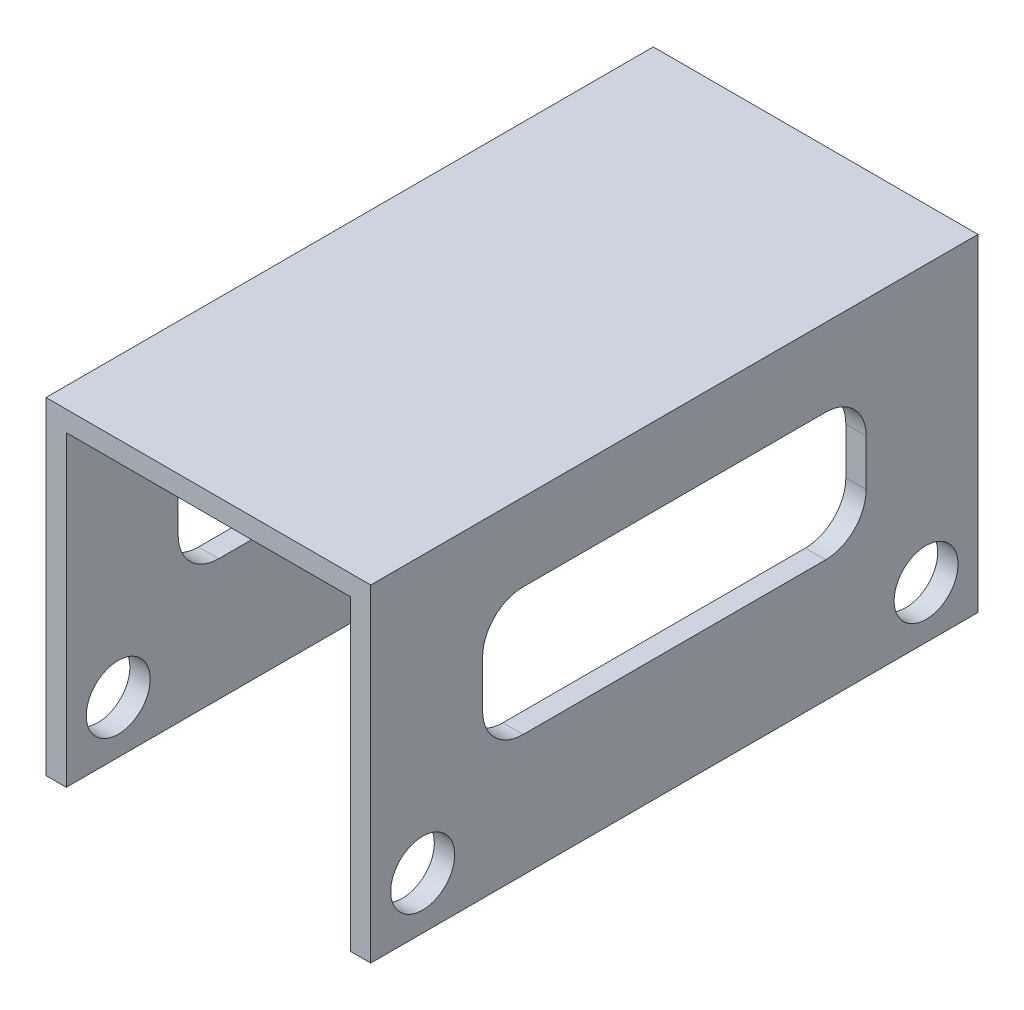
SolidWorks part; units mm, degrees
ref_plane "Front Plane" through (0, 0, 0) normal (0, 0, 1) x (1, 0, 0)
ref_plane "Top Plane" through (0, 0, 0) normal (0, 1, 0) x (1, 0, 0)
ref_plane "Right Plane" through (0, 0, 0) normal (1, 0, 0) x (0, 0, -1)
sketch "Sketch1" plane through (0, 0, 0) normal (0, 0, 1) x (1, 0, 0)
  line L1 (-25.4, -38.1) -> (25.4, -38.1)
  line L2 (-25.4, -38.1) -> (-25.4, 38.1)
  line L3 (-25.4, 38.1) -> (25.4, 38.1)
  line L4 (25.4, -38.1) -> (25.4, 38.1)
  line L5 (-25.4, -38.1) -> (25.4, 38.1) construction
  line L6 (-25.4, 38.1) -> (25.4, -38.1) construction
  line L10 (-22.225, 34.925) -> (22.225, 34.925)
  line L11 (22.225, -34.925) -> (22.225, 34.925)
  line L12 (-22.225, -34.925) -> (22.225, -34.925)
  line L13 (-22.225, -34.925) -> (-22.225, 34.925)
  point P0 (0, 0)
  dimension "D1" = 50.8
  dimension "D2" = 76.2
  dimension "D3" = 3.175
extrude "Boss-Extrude1" add sketch "Sketch1" along normal blind 95
sketch "Sketch3" plane through (0, 0, 0) normal (1, 0, 0) x (0, 0, -1)
  line L0 (0, -38.1) -> (0, 38.1) construction
  line L1 (-95, -38.1) -> (0, -38.1)
  line L2 (-95, -38.1) -> (-95, -13.125)
  line L3 (-95, -13.125) -> (0, -13.125)
  line L4 (0, -38.1) -> (0, -13.125)
  line L5 (-95, -13.125) -> (-86.875, -13.125) construction
  line L6 (-86.875, -13.125) -> (-86.875, -5) construction
  line L7 (-47.5, -13.125) -> (-47.5, 5.925) construction
  line L8 (-17.5, 5.925) -> (-17.5, 25.925)
  line L9 (-17.5, 5.925) -> (-77.5, 5.925)
  line L11 (-17.5, 25.925) -> (-77.5, 25.925)
  line L12 (-77.5, 5.925) -> (-77.5, 25.925)
  circle A0 centre (-86.875, -5) radius 5
  circle A1 centre (-8.125, -5) radius 5
  dimension "D4" = 10
  dimension "D1" = 24.975
  dimension "D2" = 8.125
  dimension "D3" = 8.125
  dimension "D5" = 19.05
  dimension "D6" = 20
  dimension "D7" = 30
extrude "Cut-Extrude2" cut sketch "Sketch3" against normal through all both and the other way through all contours L11 L12 L9 L8 | A0 | A1 | L2 L1 L4 L3
fillet "Fillet2" radius 6.35 8 edges at (-23.8125, 5.925, 77.5) (-23.8125, 25.925, 77.5) (-23.8125, 5.925, 17.5) (-23.8125, 25.925, 17.5) (23.8125, 25.925, 17.5) (23.8125, 5.925, 17.5) (23.8125, 5.925, 77.5) (23.8125, 25.925, 77.5)
